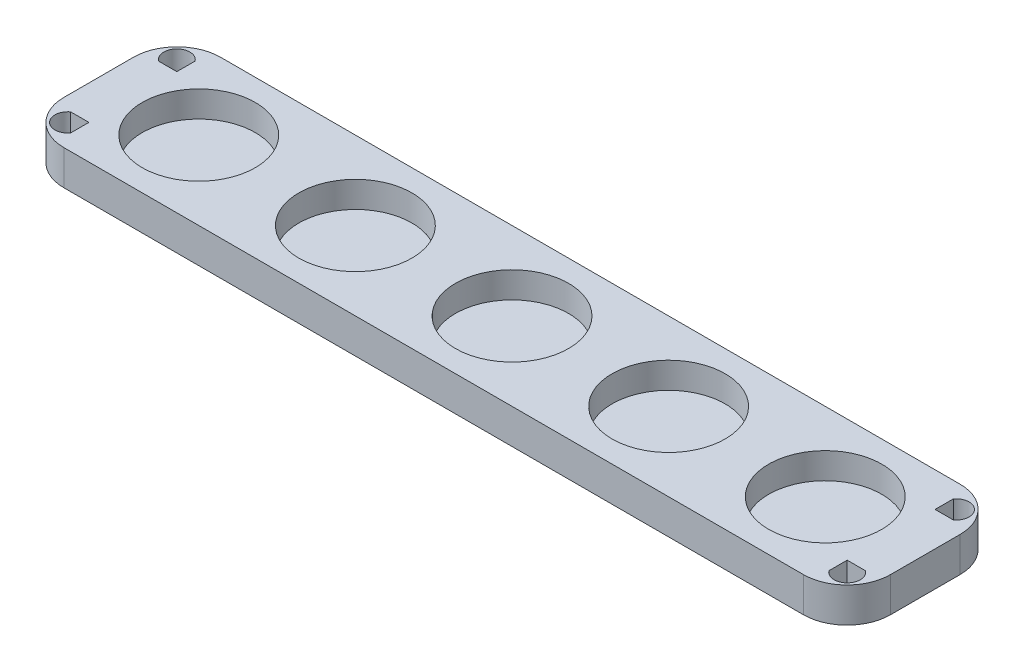
SolidWorks part; units mm, degrees
ref_plane "Front Plane" through (0, 0, 0) normal (0, 0, 1) x (1, 0, 0)
ref_plane "Top Plane" through (0, 0, 0) normal (0, 1, 0) x (1, 0, 0)
ref_plane "Right Plane" through (0, 0, 0) normal (1, 0, 0) x (0, 0, -1)
sketch "Sketch5" plane through (0, 0, 0) normal (0, 1, 0) x (1, 0, 0)
  line L1 (0, 0) -> (190, 0)
  line L2 (0, 0) -> (0, 36)
  line L3 (0, 36) -> (190, 36)
  line L4 (190, 0) -> (190, 36)
  dimension "D1" = 36
  dimension "D2" = 190
extrude "Boss-Extrude1" add sketch "Sketch5" along normal blind 8
sketch "Sketch6" plane through (0, 8, 0) normal (0, 1, 0) x (1, 0, 0)
  circle A0 centre (23, 18) radius 13
  circle A1 centre (59, 18) radius 13
  circle A2 centre (95.0046, 18) radius 13
  circle A3 centre (131.0046, 18) radius 13
  circle A4 centre (167.0023, 18) radius 12.9977
  point P6 (10, 18)
  point P7 (180, 18)
extrude "Cut-Extrude1" cut sketch "Sketch6" against normal blind 6
fillet "Fillet1" radius 10 4 edges at (190, 4, 0) (190, 4, -36) (0, 4, -36) (0, 4, 0)
sketch "Sketch9" plane through (0, 8, 0) normal (0, 1, 0) x (1, 0, 0)
  line L4 (10, 0) -> (9.8205, 7.9705)
  line L5 (0, 9.6137) -> (8, 9.5931)
  line L6 (3.6526, 7.8998) -> (7.8526, 7.8998)
  line L7 (7.8526, 7.8998) -> (7.8526, 3.6998)
  line L14 (0, 26.3863) -> (8, 26.4069)
  line L15 (10, 36) -> (9.8205, 28.0295)
  line L16 (7.8526, 28.1002) -> (7.8526, 32.3002)
  line L17 (3.6526, 28.1002) -> (7.8526, 28.1002)
  line L18 (182.1474, 7.8998) -> (182.1474, 3.6998)
  line L19 (186.3474, 7.8998) -> (182.1474, 7.8998)
  line L20 (190, 9.6137) -> (182, 9.5931)
  line L21 (180, 0) -> (180.1795, 7.9705)
  line L22 (180, 36) -> (180.1795, 28.0295)
  line L23 (190, 26.3863) -> (182, 26.4069)
  line L24 (182.1474, 28.1002) -> (182.1474, 32.3002)
  line L25 (186.3474, 28.1002) -> (182.1474, 28.1002)
  arc A3 (9.8205, 7.9705) -> (8, 9.5931) centre (10.0398, 10.0492) cw
  arc A4 (10, 0) -> (0, 9.6137) centre (10.0398, 10.0492) cw
  arc A5 (7.8526, 3.6998) -> (3.6526, 7.8998) centre (5.4465, 5.4938) cw
  arc A6 (10, 36) -> (0, 26.3863) centre (10.0398, 25.9508) ccw
  arc A7 (9.8205, 28.0295) -> (8, 26.4069) centre (10.0398, 25.9508) ccw
  arc A8 (7.8526, 32.3002) -> (3.6526, 28.1002) centre (5.4465, 30.5062) ccw
  arc A9 (182.1474, 3.6998) -> (186.3474, 7.8998) centre (184.5535, 5.4938) ccw
  arc A10 (180, 0) -> (190, 9.6137) centre (179.9602, 10.0492) ccw
  arc A11 (180.1795, 7.9705) -> (182, 9.5931) centre (179.9602, 10.0492) ccw
  arc A12 (180.1795, 28.0295) -> (182, 26.4069) centre (179.9602, 25.9508) cw
  arc A13 (180, 36) -> (190, 26.3863) centre (179.9602, 25.9508) cw
  arc A14 (182.1474, 32.3002) -> (186.3474, 28.1002) centre (184.5535, 30.5062) cw
extrude "Cut-Extrude2" cut sketch "Sketch9" against normal blind 8 contours A8 L17 L16 | L6 L7 A5 | L24 A14 L25 | A9 L19 L18
